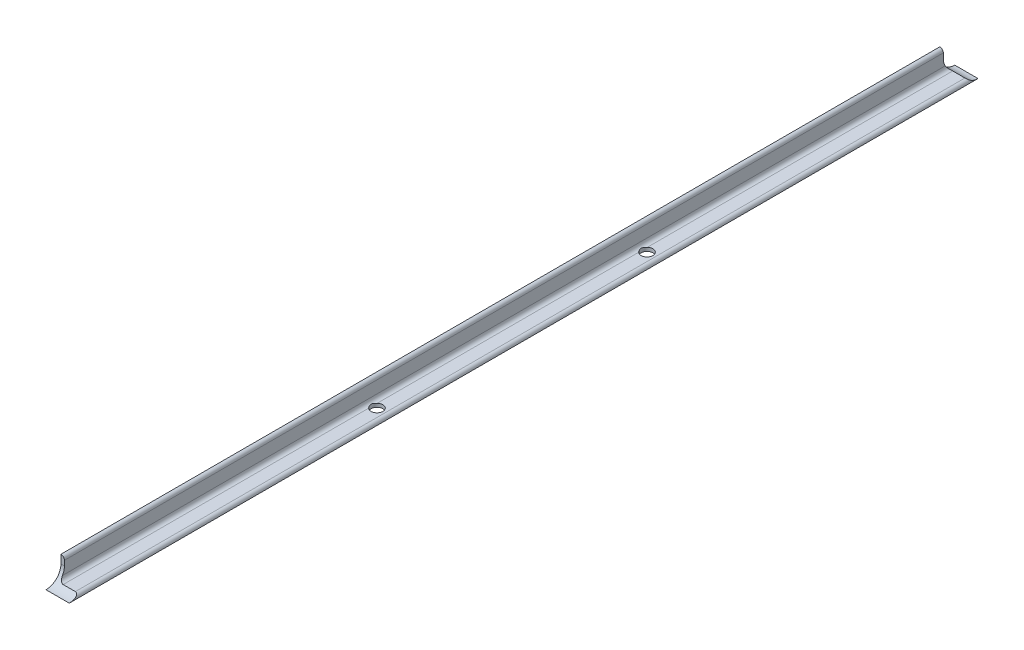
SolidWorks part; units mm, degrees
material "AISI 1010 Barra de acero laminada en caliente"
ref_plane "Alzado" through (0, 0, 0) normal (0, 0, 1) x (1, 0, 0)
ref_plane "Planta" through (0, 0, 0) normal (0, 1, 0) x (1, 0, 0)
ref_plane "Vista lateral" through (0, 0, 0) normal (1, 0, 0) x (0, 0, -1)
sketch "Croquis1" plane through (0, 0, 0) normal (0, 1, 0) x (1, 0, 0)
  line L0 (0, 599.329) -> (0, -181.371)
  dimension "D1" = 780.7
other "Miembro estructural1"
ref_plane "Plano1" through (0, 0, -599.329) normal (0, 0, 1) x (1, 0, 0)
sketch "Sketch1" plane through (0, 0, -599.329) normal (0, 0, 1) x (1, 0, 0)
  line L0 (0, 0) -> (0, 20)
  line L1 (0, 10) -> (3, 10) construction
  line L2 (3, 17) -> (3, 6.5)
  line L3 (6.5, 3) -> (17, 3)
  line L4 (10, 3) -> (10, 0) construction
  line L5 (20, 0) -> (0, 0)
  arc A0 (20, 0) -> (17, 3) centre (17, 0) ccw
  arc A1 (0, 20) -> (3, 17) centre (0, 17) cw
  arc A2 (6.5, 3) -> (3, 6.5) centre (6.5, 6.5) cw
  point P10 (10, 0)
  point P14 (0, 10)
  point P15 (3, 10)
  point P16 (10, 3)
  point P17 (3, 20)
  point P18 (20, 3)
  point P21 (0, 0)
  dimension "D2" = 3
  dimension "D3" = 20
  dimension "Radius_1" = 3.5
  dimension "D1" = 3
sketch "Croquis2" plane through (0, 0, 0) normal (1, 0, 0) x (0, 1, 0)
  line L0 (0, -599.329) -> (0, -196.9752)
  line L1 (0, -196.9752) -> (20, -196.9752)
  line L2 (20, -196.9752) -> (20, -586.529)
  line L4 (20, -586.529) -> (12.7857, -586.529)
  line L5 (0, -208.979) -> (20, -208.979) construction
  line L7 (0, 181.371) -> (0, -599.329) construction
  line L8 (20, 181.371) -> (20, -599.329) construction
  line L9 (20, 168.571) -> (12.7857, 168.571)
  line L10 (20, -220.9828) -> (20, 168.571)
  line L11 (0, -220.9828) -> (20, -220.9828)
  line L12 (0, 181.371) -> (0, -220.9828)
  arc A0 (0, -599.329) -> (12.7857, -586.529) centre (12.8, -599.329) cw
  arc A1 (0, 181.371) -> (12.7857, 168.571) centre (12.8, 181.371) ccw
  line M16 (20, -599.329) -> (0, -599.329)
  line M18 (0, 181.371) -> (20, 181.371)
  line M19 (20, 181.371) -> (20, -599.329)
  dimension "D1" = 12.8
extrude "Cortar-Extruir2" cut sketch "Croquis2" along normal through all contours A1 L9 M18 M19 | A0 L4 M16 M19
hole_wizard "Taladro de margen para 3/81" positions "Croquis5" profile "Croquis3" hole size "3/8" standard "Ansi Inch" end condition through all
sketch "Croquis5" plane through (0, 0, 0) normal (0, -1, 0) x (-1, 0, 0)
  line L7 (-10, 92.979) -> (-10, 324.979) construction
  line L10 (-20, 208.979) -> (-10, 208.979) construction
  line L11 (-20, -181.371) -> (-20, 599.329) construction
  line L13 (-10, 92.979) -> (-10, -181.371) construction
  line L14 (0, -181.371) -> (-20, -181.371) construction
  point P0 (-10, 92.979)
  point P2 (-10, 324.979)
  dimension "D1" = 232
sketch "Croquis3" plane through (10, 0, -92.979) normal (1, 0, 0) x (0, 0, -1)
  line L0 (0, 0) -> (0, 20)
  line L1 (0, 20) -> (5.0419, 20)
  line L2 (5.0419, 20) -> (5.0419, 0)
  line L5 (5.0419, 0) -> (0, 0)
  line L11 (0, -6.35) -> (0, 107.95) construction
  dimension "Diámetro de taladro hasta el siguiente" = 10.0838
  dimension "Profundidad de taladro hasta el siguiente" = 20
